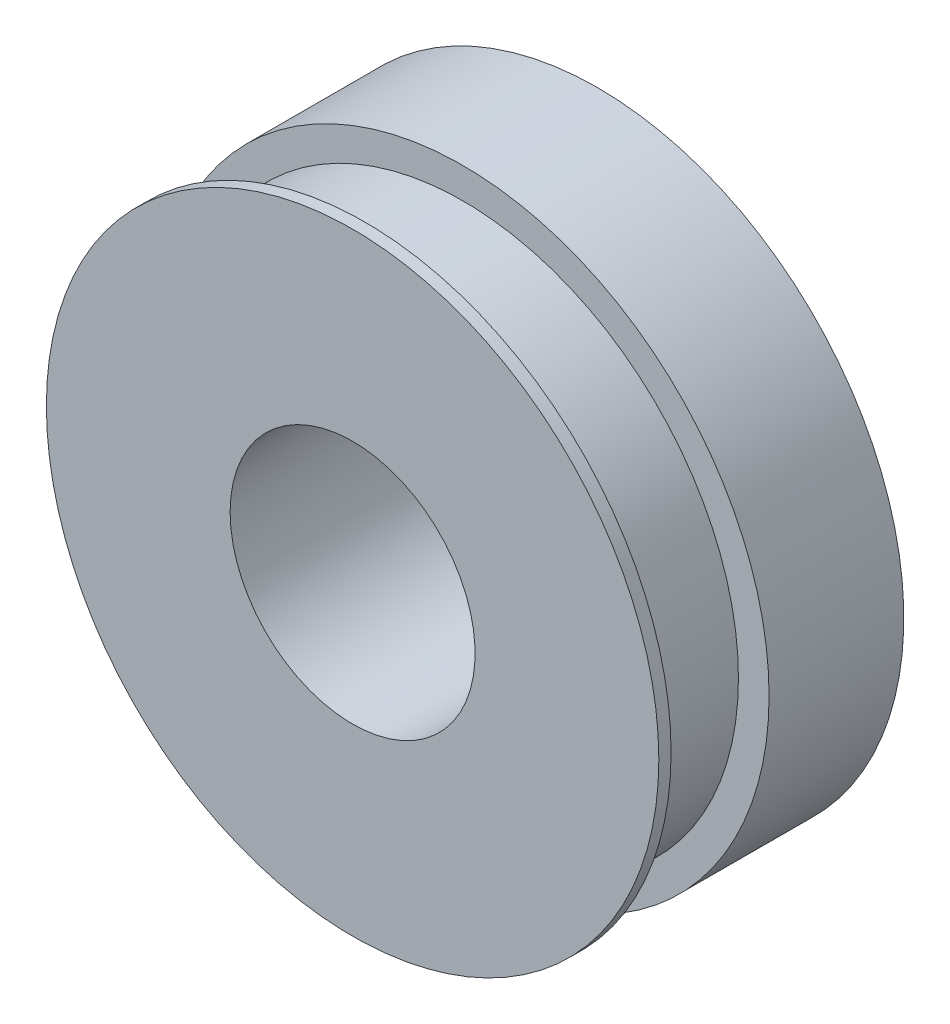
SolidWorks part; units mm, degrees
ref_plane "Front Plane" through (0, 0, 0) normal (0, 0, 1) x (1, 0, 0)
ref_plane "Top Plane" through (0, 0, 0) normal (0, 1, 0) x (1, 0, 0)
ref_plane "Right Plane" through (0, 0, 0) normal (1, 0, 0) x (0, 0, -1)
sketch "Sketch1" plane through (0, 0, 0) normal (0, 0, 1) x (1, 0, 0)
  circle A0 centre (0, 0) radius 25
  dimension "D1" = 50
extrude "Boss-Extrude1" add sketch "Sketch1" along normal blind 20
sketch "Sketch2" plane through (0, 0, 0) normal (0, 0, -1) x (-1, 0, 0)
  line L0 (-5, -20) -> (5, -20) construction
  line L1 (0, -15) -> (0, -25) construction
  circle A0 centre (0, -20) radius 5
  circle A2 centre (0, 0) radius 25 construction
  dimension "D1" = 10
extrude "Boss-Extrude2" add sketch "Sketch2" along normal blind 10
sketch "Sketch3" plane through (0, 0, 0) normal (0, 0, -1) x (-1, 0, 0)
  circle A0 centre (0, 0) radius 10
  dimension "D1" = 20
extrude "Cut-Extrude1" cut sketch "Sketch3" against normal through all
sketch "Sketch5" plane through (0, 0, 20) normal (0, 0, 1) x (1, 0, 0)
  circle A0 centre (0, 0) radius 25
  circle A1 centre (0, 0) radius 22.5
  dimension "D1" = 50
  dimension "D2" = 2.5
extrude "Cut-Extrude2" cut sketch "Sketch5" against normal blind 8 from offset 1 offset against normal yes
